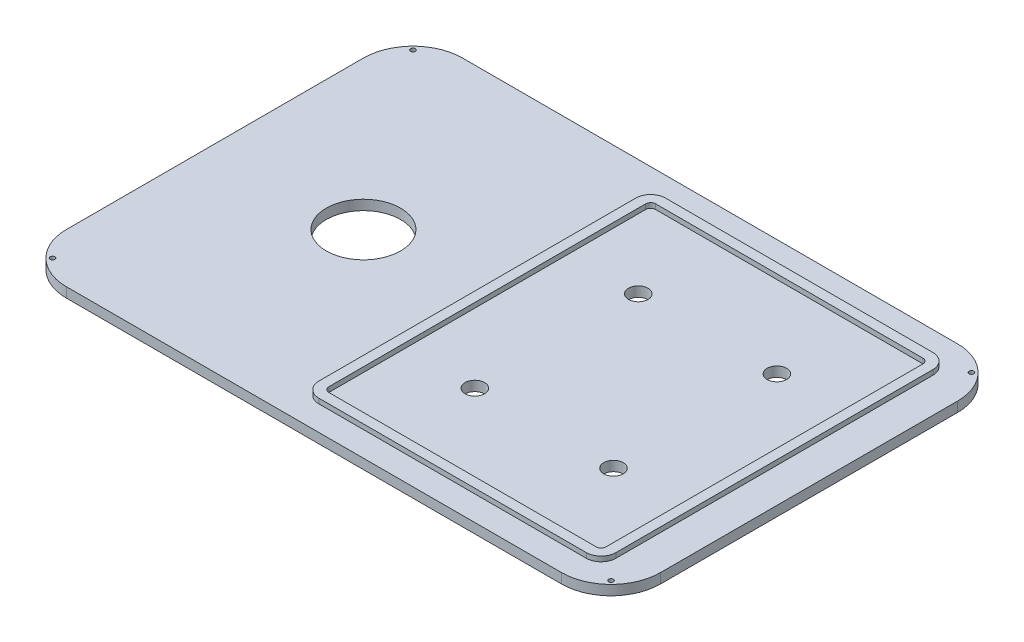
SolidWorks part; units mm, degrees
ref_plane "Front Plane" through (0, 0, 0) normal (0, 0, 1) x (1, 0, 0)
ref_plane "Top Plane" through (0, 0, 0) normal (0, 1, 0) x (1, 0, 0)
ref_plane "Right Plane" through (0, 0, 0) normal (1, 0, 0) x (0, 0, -1)
sketch "Sketch1" plane through (0, 0, 0) normal (0, 1, 0) x (1, 0, 0)
  line L1 (63.5, 50.8) -> (-63.5, 50.8)
  line L2 (76.2, 38.1) -> (76.2, -38.1)
  line L3 (63.5, -50.8) -> (-63.5, -50.8)
  line L4 (-76.2, 38.1) -> (-76.2, -38.1)
  line L5 (76.2, 50.8) -> (-76.2, -50.8) construction
  line L6 (76.2, -50.8) -> (-76.2, 50.8) construction
  arc A0 (76.2, 38.1) -> (63.5, 50.8) centre (63.5, 38.1) ccw
  arc A1 (63.5, -50.8) -> (76.2, -38.1) centre (63.5, -38.1) ccw
  arc A2 (-76.2, -38.1) -> (-63.5, -50.8) centre (-63.5, -38.1) ccw
  arc A3 (-76.2, 38.1) -> (-63.5, 50.8) centre (-63.5, 38.1) cw
  point P0 (0, 0)
  dimension "D3" = 12.7
  dimension "D1" = 152.4
  dimension "D2" = 101.6
extrude "Boss-Extrude1" add sketch "Sketch1" along normal blind 2.54
sketch "Sketch2" plane through (0, 2.54, 0) normal (0, 1, 0) x (1, 0, 0)
  line L0 (63.5, 50.8) -> (-63.5, 50.8) construction
  line L1 (-76.2, 38.1) -> (-76.2, -38.1) construction
  line L2 (-63.5, -50.8) -> (63.5, -50.8) construction
  line L3 (76.2, -38.1) -> (76.2, 38.1) construction
  circle A0 centre (-71.628, 46.228) radius 0.6
  circle A1 centre (-71.628, -46.228) radius 0.6
  circle A2 centre (71.628, -46.228) radius 0.6
  circle A3 centre (71.628, 46.228) radius 0.6
  dimension "D1" = 1.2
  dimension "D4" = 1.2
  dimension "D7" = 1.2
  dimension "D10" = 1.2
  dimension "D2" = 4.572
  dimension "D3" = 4.572
  dimension "D5" = 4.572
  dimension "D6" = 4.572
  dimension "D8" = 4.572
  dimension "D9" = 4.572
  dimension "D11" = 4.572
  dimension "D12" = 4.572
extrude "Cut-Extrude1" cut sketch "Sketch2" against normal through all
sketch "Sketch3" plane through (0, 2.54, 0) normal (0, 1, 0) x (1, 0, 0)
  line L0 (76.2, -38.1) -> (76.2, 38.1) construction
  line L1 (63.5, 44.45) -> (-5.08, 44.45)
  line L2 (67.31, 40.64) -> (67.31, -40.64)
  line L3 (63.5, -44.45) -> (-5.08, -44.45)
  line L4 (-8.89, 40.64) -> (-8.89, -40.64)
  line L5 (63.5, 50.8) -> (-63.5, 50.8) construction
  arc A0 (-5.08, -44.45) -> (-8.89, -40.64) centre (-5.08, -40.64) cw
  arc A1 (67.31, -40.64) -> (63.5, -44.45) centre (63.5, -40.64) cw
  arc A2 (63.5, 44.45) -> (67.31, 40.64) centre (63.5, 40.64) cw
  arc A3 (-8.89, 40.64) -> (-5.08, 44.45) centre (-5.08, 40.64) cw
  point P10 (-8.89, -44.45)
  point P13 (67.31, -44.45)
  point P18 (-8.89, 44.45)
  dimension "D5" = 3.81
  dimension "D1" = 76.2
  dimension "D2" = 88.9
  dimension "D3" = 8.89
  dimension "D4" = 6.35
extrude "Boss-Extrude2" add sketch "Sketch3" along normal blind 1.27
sketch "Sketch4" plane through (0, 3.81, 0) normal (0, 1, 0) x (1, 0, 0)
  line L0 (63.5, 44.45) -> (-5.08, 44.45) construction
  line L1 (-5.08, 41.91) -> (63.5, 41.91)
  line L2 (-6.35, 40.64) -> (-6.35, -40.64)
  line L3 (-5.08, -41.91) -> (63.5, -41.91)
  line L4 (64.77, 40.64) -> (64.77, -40.64)
  line L5 (-8.89, 40.64) -> (-8.89, -40.64) construction
  line L6 (67.31, -40.64) -> (67.31, 40.64) construction
  line L7 (-5.08, -44.45) -> (63.5, -44.45) construction
  arc A0 (-6.35, -40.64) -> (-5.08, -41.91) centre (-5.08, -40.64) ccw
  arc A1 (64.77, -40.64) -> (63.5, -41.91) centre (63.5, -40.64) cw
  arc A2 (64.77, 40.64) -> (63.5, 41.91) centre (63.5, 40.64) ccw
  arc A3 (-5.08, 41.91) -> (-6.35, 40.64) centre (-5.08, 40.64) ccw
  dimension "D5" = 1.27
  dimension "D1" = 2.54
  dimension "D2" = 2.54
  dimension "D3" = 2.54
  dimension "D4" = 2.54
extrude "Cut-Extrude2" cut sketch "Sketch4" against normal blind 1.27
sketch "Sketch5" plane through (0, 2.54, 0) normal (0, 1, 0) x (1, 0, 0)
  line L0 (63.5, 41.91) -> (-5.08, 41.91) construction
  line L1 (-5.08, -41.91) -> (63.5, -41.91) construction
  line L2 (-6.35, 40.64) -> (-6.35, -40.64) construction
  line L3 (64.77, -40.64) -> (64.77, 40.64) construction
  line L4 (-6.35, 40.64) -> (-6.35, -40.64) construction
  line L5 (64.77, -40.64) -> (64.77, 40.64) construction
  circle A0 centre (11.43, 20.955) radius 2.5
  circle A1 centre (46.99, 20.955) radius 2.5
  circle A2 centre (11.43, -20.955) radius 2.5
  circle A3 centre (46.99, -20.955) radius 2.5
  dimension "D1" = 5
  dimension "D4" = 5
  dimension "D5" = 5
  dimension "D6" = 5
  dimension "D2" = 17.78
  dimension "D3" = 20.955
  dimension "D7" = 20.955
  dimension "D8" = 20.955
  dimension "D9" = 20.955
  dimension "D10" = 17.78
  dimension "D11" = 17.78
  dimension "D12" = 17.78
extrude "Cut-Extrude3" cut sketch "Sketch5" against normal through all
sketch "Sketch6" plane through (0, 2.54, 0) normal (0, 1, 0) x (1, 0, 0)
  line L0 (-63.5, -50.8) -> (63.5, -50.8) construction
  line L2 (-76.2, 38.1) -> (-76.2, -38.1) construction
  circle A0 centre (-38.1, 0) radius 9.525
  dimension "D3" = 19.05
  dimension "D1" = 50.8
  dimension "D2" = 38.1
extrude "Cut-Extrude4" cut sketch "Sketch6" against normal blind 10.16
